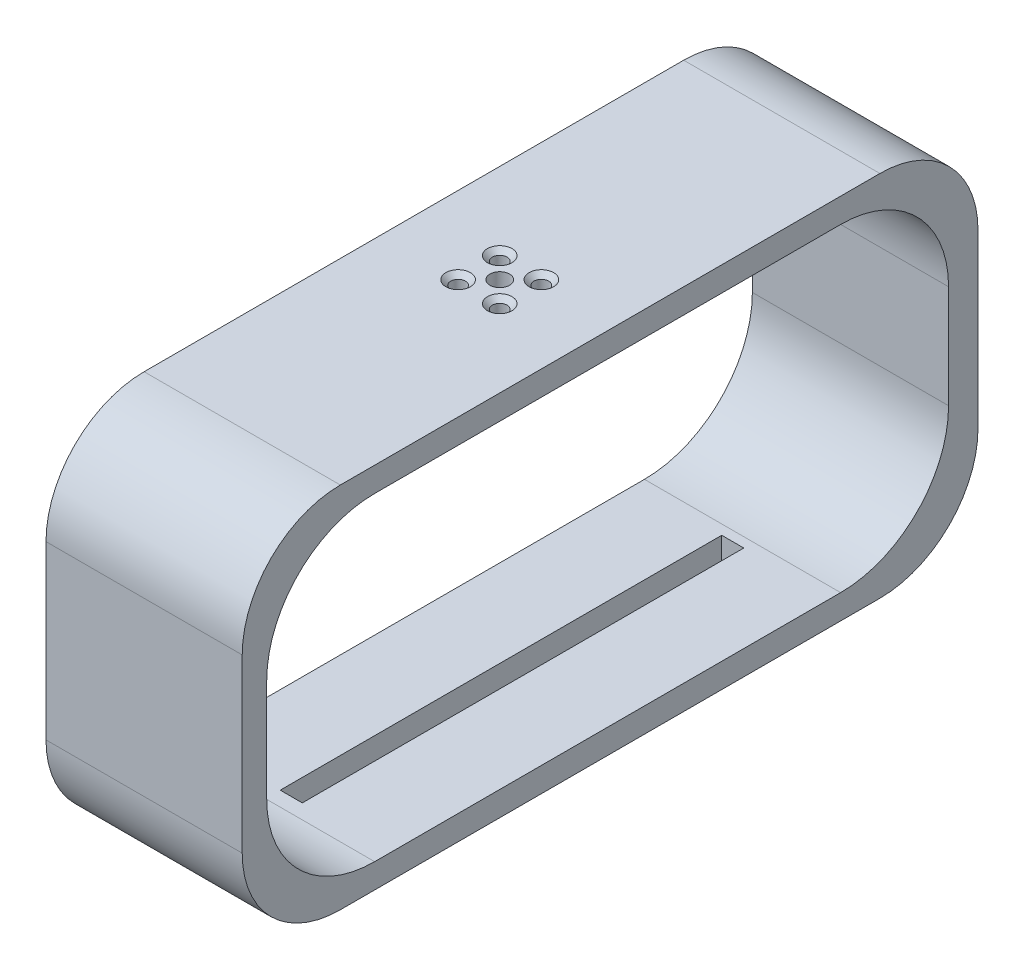
SolidWorks part; units mm, degrees
material "Polylactic Acid (PLA)"
ref_plane "Front Plane" through (0, 0, 0) normal (0, 0, 1) x (1, 0, 0)
ref_plane "Top Plane" through (0, 0, 0) normal (0, 1, 0) x (1, 0, 0)
ref_plane "Right Plane" through (0, 0, 0) normal (1, 0, 0) x (0, 0, -1)
sketch "Sketch1" plane through (0, 0, 0) normal (1, 0, 0) x (0, 0, -1)
  line L0 (0, 0) -> (150, 0)
  line L1 (55, 0) -> (-55, 0) construction
  line L2 (150, 0) -> (150, 3)
  line L3 (144, 5) -> (5, 5)
  line L4 (5, 5) -> (5, 70)
  line L5 (5, 70) -> (120, 70)
  line L7 (120, 75) -> (0, 75)
  line L8 (0, 55) -> (0, -55) construction
  line L9 (0, 75) -> (0, 0)
  line L10 (150, 3) -> (150, 75)
  line L11 (150, 75) -> (120, 75)
  line L12 (120, 70) -> (144, 70)
  line L13 (144, 70) -> (144, 5)
  dimension "D1" = 5
  dimension "D2" = 5
  dimension "D3" = 5
  dimension "D4" = 150
  dimension "D5" = 6
  dimension "D6" = 65
extrude "Boss-Extrude1" add sketch "Sketch1" along normal mid plane 40
sketch "Sketch3" plane through (0, 0, 0) normal (0, -1, 0) x (1, 0, 0)
  line L1 (0, -55) -> (0, 55) construction
  line L2 (2.25, -30) -> (2.25, -120)
  line L3 (2.25, -120) -> (-2.25, -120)
  line L4 (-2.25, -120) -> (-2.25, -30)
  line L5 (-2.25, -30) -> (2.25, -30)
  line L6 (55, 0) -> (-55, 0) construction
  line L7 (20, -150) -> (-20, -150) construction
  dimension "D1" = 2.25
  dimension "D2" = 2.25
  dimension "D3" = 30
  dimension "D4" = 30
extrude "Cut-Extrude2" cut sketch "Sketch3" against normal blind 10
sketch "Sketch4" plane through (0, 75, 0) normal (0, 1, 0) x (1, 0, 0)
  line L0 (-22, 0) -> (22, 0) construction
  line L1 (0, 72.5) -> (-4.2426, 76.7426) construction
  line L2 (0, 72.5) -> (4.2426, 76.7426) construction
  line L3 (0, -41.25) -> (0, 41.25) construction
  line L4 (-4.2426, 76.7426) -> (-4.2426, 68.2574) construction
  line L6 (20, 150) -> (-20, 150) construction
  circle A0 centre (-4.2426, 76.7426) radius 1.5
  circle A1 centre (4.2426, 76.7426) radius 1.5
  circle A2 centre (4.2426, 68.2574) radius 1.5
  circle A3 centre (-4.2426, 68.2574) radius 1.5
  circle A4 centre (0, 72.5) radius 2
  dimension "D1" = 72.5
  dimension "D5" = 73.2574
  dimension "D3" = 90
  dimension "D4" = 0
  dimension "D2" = 4
extrude "Cut-Extrude3" cut sketch "Sketch4" against normal blind 10
chamfer "Chamfer1" distance 1 angle 45 4 edges at (4.2426, 75, -66.7574) (4.2426, 75, -75.2426) (-4.2426, 75, -75.2426) (-4.2426, 75, -66.7574)
fillet "Fillet1" radius 22 4 edges at (0, 5, -144) (0, 70, -144) (0, 5, -5) (0, 70, -5)
fillet "Fillet2" radius 20 4 edges at (0, 0, -150) (0, 75, -150) (0, 0, 0) (0, 75, 0)
